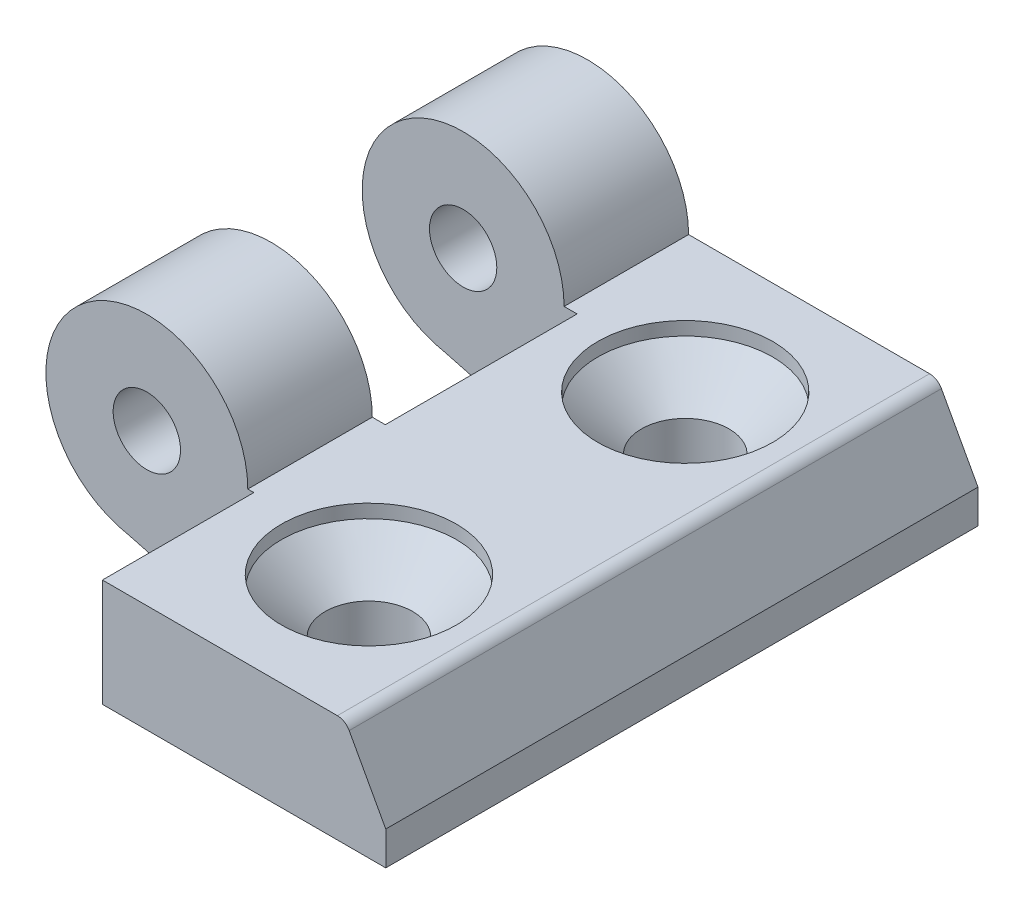
SolidWorks part; units mm, degrees
ref_plane "前视基准面" through (0, 0, 0) normal (0, 0, 1) x (1, 0, 0)
ref_plane "上视基准面" through (0, 0, 0) normal (0, 1, 0) x (1, 0, 0)
ref_plane "右视基准面" through (0, 0, 0) normal (1, 0, 0) x (0, 0, -1)
sketch "草图1" plane through (0, 0, 0) normal (0, 0, 1) x (1, 0, 0)
  line B0 (29, -5.5) -> (29, -8)
  line B1 (25.4064, 0) -> (7.5, 0)
  line B2 (29, -8) -> (1, -8)
  line B3 (29, -5.5) -> (26.2843, -0.5211)
  line B4 (1, -8) -> (-1.3701, -7.3738)
  arc B5 (7.5, 0) -> (-1.3701, -7.3738) centre (0, 0) ccw
  arc B6 (26.2843, -0.5211) -> (25.4064, 0) centre (25.4064, -1) ccw
sketch_block_instance "A$C603C625E-1"
sketch_block "A$C603C625E"
extrude "凸台-拉伸1" add sketch "草图1" along normal mid plane 44
ref_plane "基准面2" through (0, 0, 11.75) normal (0, 0, 1) x (1, 0, 0)
sketch "草图3" plane through (0, 0, 11.75) normal (0, 0, 1) x (1, 0, 0)
  line L2 (24, 0) -> (17.5, 0)
  line L10 (24, -1) -> (20.75, -4)
  line L11 (24, -1) -> (24, 0)
  line L12 (17.5, -8) -> (17.5, 0)
  line L13 (20.75, -4) -> (20.75, -8)
  line L14 (20.75, -8) -> (17.5, -8)
revolve "切除-旋转1" cut sketch "草图3" angle 360 about L12
pattern_linear "阵列(线性)1" count 2 spacing 23.5 along (0, 0, -1) of "切除-旋转1"
sketch "草图4" plane through (0, 0, 0) normal (0, 1, 0) x (1, 0, 0)
  line L0 (-25.4064, -22) -> (-7.5, -22) construction
  line L1 (-7.9432, -22) -> (7.9514, -22)
  line L2 (-7.9432, -22) -> (-7.9432, -10.75)
  line L3 (-7.9432, -10.75) -> (7.9514, -10.75)
  line L4 (7.9514, -22) -> (7.9514, -10.75)
  line L6 (-7.5, -0.5) -> (7.5, -0.5) construction
  line L8 (-7.9432, 12.75) -> (8.4662, 12.75)
  line L9 (-7.9432, 12.75) -> (-7.9432, -1.5)
  line L10 (-7.9432, -1.5) -> (8.4662, -1.5)
  line L11 (8.4662, 12.75) -> (8.4662, -1.5)
  line L12 (7.5, 11.75) -> (-7.5, 11.75) construction
  dimension "D1" = 11.25
  dimension "D3" = 1
  dimension "D2" = 1
extrude "切除-拉伸1" cut sketch "草图4" against normal through all and the other way through all
sketch "草图5" plane through (0, 0, 10.75) normal (0, 0, 1) x (1, 0, 0)
  circle A0 centre (0, 0) radius 2.5
extrude "切除-拉伸2" cut sketch "草图5" against normal through all
